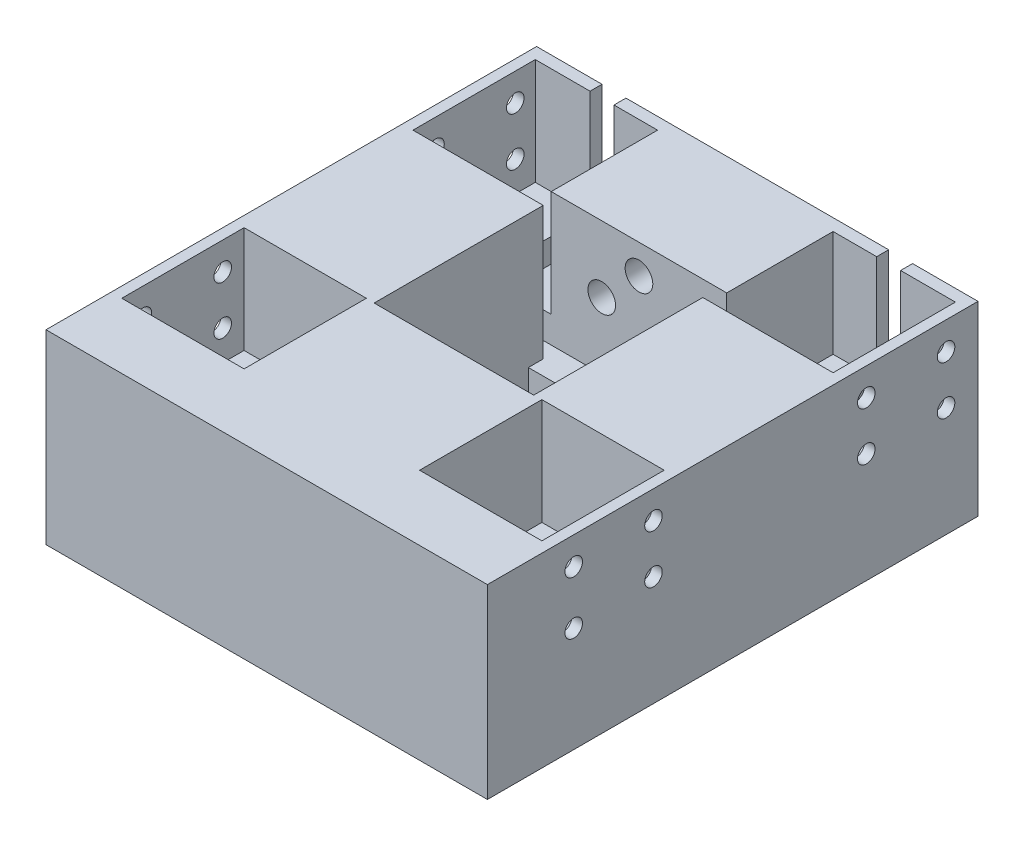
SolidWorks part; units mm, degrees
material "ABS"
ref_plane "前视基准面" through (0, 0, 0) normal (0, 0, 1) x (1, 0, 0)
ref_plane "上视基准面" through (0, 0, 0) normal (0, 1, 0) x (1, 0, 0)
ref_plane "右视基准面" through (0, 0, 0) normal (1, 0, 0) x (0, 0, -1)
sketch "Sketch2" plane through (0, 0, 0) normal (0, 1, 0) x (1, 0, 0)
  line L1 (-41.5, 40) -> (41.5, 40)
  line L2 (-41.5, 40) -> (-41.5, -40)
  line L3 (-41.5, -40) -> (41.5, -40)
  line L4 (41.5, 40) -> (41.5, -40)
  line L5 (0, -40) -> (0, 40) construction
  line L6 (-41.5, 0) -> (41.5, 0) construction
  point P0 (0, 0)
  dimension "D1" = 83
  dimension "D2" = 80
extrude "Boss-Extrude1" add sketch "Sketch2" along normal blind 35
sketch "Sketch3" plane through (0, 35, 0) normal (0, 1, 0) x (1, 0, 0)
  line L0 (41.5, -40) -> (41.5, 40) construction
  line L1 (39.5, -37.7546) -> (16.5, -37.7546)
  line L2 (39.5, -37.7546) -> (39.5, -14.7546)
  line L3 (39.5, -14.7546) -> (16.5, -14.7546)
  line L4 (16.5, -37.7546) -> (16.5, -14.7546)
  line L5 (-41.5, -40) -> (41.5, -40) construction
  line L6 (39.5, 17) -> (16.5, 17)
  line L7 (39.5, 17) -> (39.5, 40)
  line L8 (39.5, 40) -> (16.5, 40)
  line L9 (16.5, 17) -> (16.5, 40)
  line L10 (41.5, 40) -> (-41.5, 40) construction
  dimension "D1" = 23
  dimension "D2" = 23
  dimension "20" = 23
  dimension "D3" = 2
  dimension "D4" = 2.2454
  dimension "D5" = 23
  dimension "D6" = 2
  dimension "D7" = 0
extrude "Cut-Extrude1" cut sketch "Sketch3" against normal blind 20
sketch "Sketch21" plane through (39.5, 0, 0) normal (-1, 0, 0) x (0, 0, 1)
  circle A16 centre (-36.2416, 29.797) radius 1.65
  circle A17 centre (-36.2416, 20.6663) radius 1.65
  circle A18 centre (-21.2416, 29.797) radius 1.65
  circle A19 centre (-21.2416, 20.6663) radius 1.65
  circle A20 centre (18.7715, 29.797) radius 1.65
  circle A21 centre (33.7715, 29.797) radius 1.65
  circle A22 centre (33.7715, 19.797) radius 1.65
  circle A23 centre (18.7715, 20.6663) radius 1.65
  dimension "D1" = 3.3
extrude "Cut-Extrude11" cut sketch "Sketch21" against normal up to next
sketch "Sketch8" plane through (0, 35, 0) normal (0, 1, 0) x (1, 0, 0)
  line L0 (-15, 14.2) -> (0, 14.2)
  line L1 (-41.5, -0.3) -> (41.5, -0.3) construction
  line L2 (41.5, -40) -> (41.5, 40) construction
  line L3 (-41.5, 40) -> (-41.5, -40) construction
  line L4 (15, 14.2) -> (0, 14.2)
  line L5 (15, 14.2) -> (15, -14.8)
  line L6 (0, 14.2) -> (0, -14.8)
  line L7 (15, -14.8) -> (0, -14.8)
  line L8 (15, 14.2) -> (0, -14.8) construction
  line L9 (0, 14.2) -> (15, -14.8) construction
  line L11 (-15, 14.2) -> (-15, -14.8)
  line L12 (0, 14.2) -> (0, -14.8)
  line L14 (-15, 14.2) -> (0, -14.8) construction
  line L15 (0, 14.2) -> (-15, -14.8) construction
  line L16 (9.1402, -14.8) -> (-15, -14.8)
  point P2 (0, -0.3)
  point P3 (-7.5, -0.3)
  point P4 (0, -0.3)
  point P11 (7.5, -0.3)
  point P18 (-15, -0.3)
  dimension "D1" = 29
  dimension "D2" = 15
  dimension "D3" = 15
  dimension "D4" = 29
extrude "Cut-Extrude3" cut sketch "Sketch8" against normal up to next
sketch "Sketch10" plane through (15, 0, 0) normal (-1, 0, 0) x (0, 0, 1)
  line L0 (-14.2, 35) -> (14.8, 35) construction
  line L1 (14.8, 0) -> (14.8, 35) construction
  line B0 (8.8, 30) -> (8.8, 5) construction
  line B1 (-7.2, 30) -> (8.8, 30) construction
  line B2 (-7.2, 30) -> (-7.2, 5) construction
  line B3 (-7.2, 5) -> (8.8, 5) construction
  line B4 (0.8, 5) -> (0.8, 30) construction
  line B5 (-7.2, 17.5) -> (8.8, 17.5) construction
  circle B6 centre (8.8, 30) radius 3.35
  circle B7 centre (8.8, 5) radius 3.35
  circle B8 centre (-7.2, 5) radius 3.35
  circle B9 centre (-7.2, 30) radius 3.35
  dimension "D1" = 17.5
  dimension "D2" = 14
sketch_block_instance "Block2-1"
sketch_block "Block2" parameters "D1"=2.9252, "D2"=17.0778, "D3"=34.0855, "D4"=20.3
extrude "Cut-Extrude4" cut sketch "Sketch10" against normal blind 12
sketch "Sketch11" plane through (0, 0, -40) normal (0, 0, -1) x (-1, 0, 0)
  line L1 (-41.5, 35) -> (41.5, 35)
  line L2 (-41.5, 35) -> (-41.5, 0)
  line L3 (-41.5, 0) -> (41.5, 0)
  line L4 (41.5, 35) -> (41.5, 0)
extrude "Boss-Extrude2" add sketch "Sketch11" along normal blind 2.25
mirror "Mirror1" about plane through (0, 0, 0) normal (1, 0, 0) of "Cut-Extrude1", "Cut-Extrude11"
sketch "Sketch24" plane through (0, 35, 0) normal (0, 1, 0) x (1, 0, 0)
  line L1 (-29.1988, 20) -> (29.1988, 20)
  line L2 (-29.1988, 20) -> (-29.1988, 17)
  line L3 (-29.1988, 17) -> (29.1988, 17)
  line L4 (29.1988, 20) -> (29.1988, 17)
  line L5 (0, 17) -> (0, 20) construction
  line L6 (-29.1988, 18.5) -> (29.1988, 18.5) construction
  line L7 (-15, 14.2) -> (15, 14.2) construction
  point P0 (0, 18.5)
  dimension "D1" = 3
  dimension "D2" = 2.8
extrude "Cut-Extrude13" cut sketch "Sketch24" against normal blind 25
sketch "Sketch25" plane through (0, 35, 0) normal (0, 1, 0) x (1, 0, 0)
  line L0 (15, 14.2) -> (15, -14.8) construction
  line L1 (-15, 17.5634) -> (15, 17.5634)
  line L2 (-15, 17.5634) -> (-15, 14.2)
  line L3 (-15, 14.2) -> (15, 14.2)
  line L4 (15, 17.5634) -> (15, 14.2)
  line L5 (0, 14.2) -> (0, 17.5634) construction
  line L6 (-15, 15.8817) -> (15, 15.8817) construction
  line L7 (-15, 14.2) -> (15, 14.2) construction
  point P0 (0, 15.8817)
extrude "Cut-Extrude14" cut sketch "Sketch25" against normal up to surface (25 mm away) up to face at (0, 10, -18.5)
sketch "Sketch28" plane through (0, 35, 0) normal (0, 1, 0) x (1, 0, 0)
  line L0 (29.1988, 20) -> (-29.1988, 20) construction
  line L1 (-29.1988, 20) -> (-24.6988, 20)
  line L2 (-29.1988, 20) -> (-29.1988, 42.25)
  line L3 (-29.1988, 42.25) -> (-24.6988, 42.25)
  line L4 (-24.6988, 20) -> (-24.6988, 42.25)
  line L5 (-29.1988, 20) -> (-29.1988, 17) construction
  line L6 (-41.5, 42.25) -> (41.5, 42.25) construction
  line L7 (0, -19.25) -> (0, 19.25) construction
  line L8 (24.6988, 20) -> (24.6988, 42.25)
  line L9 (29.1988, 42.25) -> (24.6988, 42.25)
  line L10 (29.1988, 20) -> (29.1988, 42.25)
  line L11 (29.1988, 20) -> (24.6988, 20)
  dimension "D1" = 4.5
extrude "Cut-Extrude15" cut sketch "Sketch28" against normal up to surface (25 mm away) up to face at (0, 10, -17.05)
fillet "Fillet2" radius 2 2 edges at (-24.6988, 12.5, -20) (24.6988, 12.5, -20)
sketch "Sketch29" plane through (0, 0, -20) normal (0, 0, 1) x (1, 0, 0)
  circle A8 centre (0, 29.5) radius 2.6
  circle A9 centre (-7, 22.5) radius 2.6
  circle A10 centre (7, 22.5) radius 2.6
  circle A11 centre (0, 15.5) radius 2.6
  dimension "D1" = 5.2
extrude "Cut-Extrude16" cut sketch "Sketch29" against normal blind 8
sketch "Sketch30" plane through (0, 0, -17) normal (0, 0, -1) x (-1, 0, 0)
  circle A4 centre (-18.6, 22.5) radius 2.6
  circle A5 centre (18.6, 22.5) radius 2.6
  dimension "D1" = 5.2
extrude "Cut-Extrude17" cut sketch "Sketch30" against normal blind 8
sketch "Sketch32" plane through (0, 0, 40) normal (0, 0, 1) x (1, 0, 0)
  line L0 (-41.5, 35) -> (41.5, 35) construction
  line L1 (41.5, 35) -> (-41.5, 35)
  line L2 (41.5, 35) -> (41.5, 0)
  line L3 (41.5, 0) -> (-41.5, 0)
  line L4 (-41.5, 35) -> (-41.5, 0)
  line L5 (41.5, 35) -> (41.5, 0) construction
  line L6 (-41.5, 0) -> (41.5, 0) construction
extrude "Boss-Extrude5" add sketch "Sketch32" along normal blind 10
